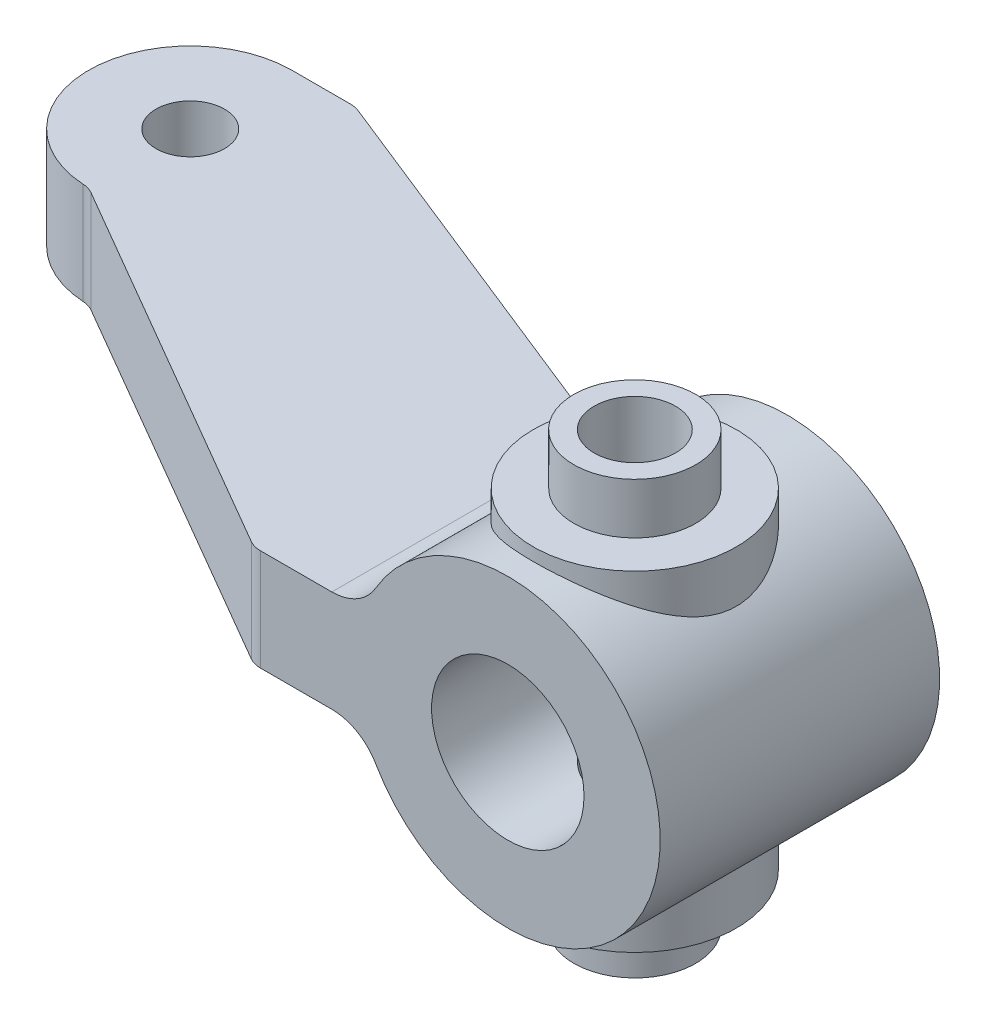
SolidWorks part; units mm, degrees
ref_plane "Front Plane" through (0, 0, 0) normal (0, 0, 1) x (1, 0, 0)
ref_plane "Top Plane" through (0, 0, 0) normal (0, 1, 0) x (1, 0, 0)
ref_plane "Right Plane" through (0, 0, 0) normal (1, 0, 0) x (0, 0, -1)
sketch "Sketch1" plane through (0, 0, 0) normal (0, 0, 1) x (1, 0, 0)
  line L0 (0, 9.7727) -> (0, -10.2276) construction
  line L1 (1.6, -8.5) -> (1.6, 8.5)
  line L2 (1.6, 8.5) -> (2.4, 8.5)
  line L3 (2.4, 8.5) -> (2.4, 6.5)
  line L4 (2.4, 6.5) -> (4, 6.5)
  line L5 (4, 6.5) -> (4, -6.5)
  line L7 (2.4, -6.5) -> (4, -6.5)
  line L8 (2.4, -8.5) -> (2.4, -6.5)
  line L9 (-0.9044, 0) -> (7.5503, 0) construction
  line L10 (1.6, -8.5) -> (2.4, -8.5)
  dimension "D1" = 17
  dimension "D2" = 13
  dimension "D3" = 3.2
  dimension "D4" = 8
  dimension "D5" = 4.8
revolve "Revolve1" add sketch "Sketch1" angle 360 about L0
sketch "Sketch2" plane through (0, 0, 0) normal (0, 0, 1) x (1, 0, 0)
  circle A0 centre (0, 0) radius 6
  dimension "D1" = 12
extrude "Boss-Extrude1" add sketch "Sketch2" along normal blind 5 and the other way blind 6
sketch "Sketch3" plane through (0, 0, 0) normal (0, 0, 1) x (1, 0, 0)
  circle A1 centre (0, 0) radius 3
  dimension "D1" = 6
extrude "Cut-Extrude1" cut sketch "Sketch3" against normal up to next and the other way up to next
sketch "Sketch4" plane through (0, 8.5, 0) normal (0, 1, 0) x (1, 0, 0)
  circle A0 centre (0, 0) radius 1.6
  circle A1 centre (0, 0) radius 1.6 construction
extrude "Cut-Extrude4" cut sketch "Sketch4" against normal up to surface (17 mm away) up to face at (-2.4, -8.5, 0)
sketch "Sketch5" plane through (0, 0, 0) normal (0, 1, 0) x (1, 0, 0)
  line L0 (-6, -5) -> (-10, -5)
  line L1 (-10, -5) -> (-25.5, 4)
  line L2 (-6, 6) -> (-8, 6)
  line L3 (-8, 6) -> (-23, 12)
  line L4 (-23, 12) -> (-25.5, 12)
  line L5 (6, -5) -> (6, 6) construction
  line L6 (6, 6) -> (6, -5) construction
  line L7 (6, 6) -> (-6, 6) construction
  line L8 (-6, 6) -> (-3, 6)
  line L9 (-6, -5) -> (6, -5) construction
  line L10 (3, 6) -> (-3, 6) construction
  line L11 (-3, 6) -> (-3, -5)
  line L12 (-3, -5) -> (3, -5) construction
  line L13 (-3, -5) -> (-6, -5)
  arc A0 (-25.5, 12) -> (-25.5, 4) centre (-25.5, 8) ccw
  circle A1 centre (-25.5, 8) radius 1.35
  dimension "D1" = 4
  dimension "D3" = 16
  dimension "D7" = 2.7
  dimension "D2" = 31.5
  dimension "D4" = 14
  dimension "D5" = 2
  dimension "D6" = 2.5
extrude "Boss-Extrude2" add sketch "Sketch5" along normal blind 2 and the other way blind 2
fillet "Fillet1" radius 2 2 edges at (-5.6569, -2, -0.5) (-5.6569, 2, -0.5)
fillet "Fillet2" radius 1 4 edges at (-8, 0, -6) (-10, 0, 5) (-25.5, 0, -4) (-23, 0, -12)
